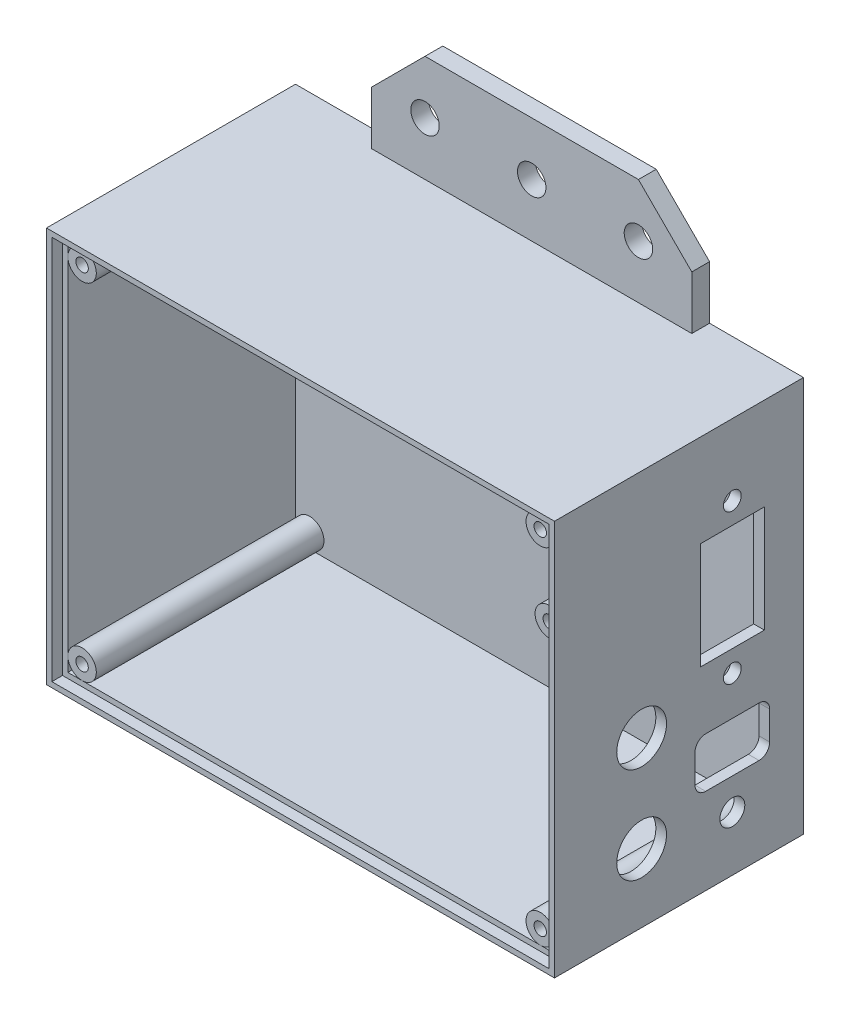
SolidWorks part; units mm, degrees
ref_plane "Alzado" through (0, 0, 0) normal (0, 0, 1) x (1, 0, 0)
ref_plane "Planta" through (0, 0, 0) normal (0, 1, 0) x (1, 0, 0)
ref_plane "Vista lateral" through (0, 0, 0) normal (1, 0, 0) x (0, 0, -1)
sketch "Croquis2" plane through (0, 0, 0) normal (0, 0, 1) x (1, 0, 0)
  line L0 (-57.8, 5) -> (-57.8, -61.2) construction
  line L1 (-57.8, -61.2) -> (5, -61.2) construction
  line L2 (5, -61.2) -> (5, 5) construction
  line L3 (-97.8, -76.2) -> (45, -76.2)
  line L4 (-57.8, 5) -> (5, 5) construction
  line L5 (-97.8, 35) -> (45, 35)
  line L6 (-97.8, 35) -> (-97.8, -76.2)
  line L7 (45, -76.2) -> (45, 35)
  circle A0 centre (0, 0) radius 1.75
  circle A1 centre (-50.8, -11.75) radius 1.75
  circle A2 centre (-16.46, -50.2) radius 1.75
extrude "Saliente-Extruir1" add sketch "Croquis2" along normal blind 3
sketch "Croquis3" plane through (0, 0, 0) normal (0, 0, 1) x (1, 0, 0)
  line L1 (-97.8, 35) -> (45, 35)
  line L2 (-97.8, 35) -> (-97.8, -76.2)
  line L3 (-97.8, -76.2) -> (45, -76.2)
  line L4 (45, 35) -> (45, -76.2)
  line L9 (-94.8, 32) -> (42, 32)
  line L10 (-94.8, 32) -> (-94.8, -73.2)
  line L11 (-94.8, -73.2) -> (42, -73.2)
  line L12 (42, 32) -> (42, -73.2)
  circle A0 centre (-90.8, 28) radius 1.75
  circle A1 centre (-90.8, 28) radius 4
  circle A2 centre (-90.8, -69.2) radius 1.75
  circle A3 centre (-90.8, -69.2) radius 4
  circle A4 centre (38, -69.2) radius 1.75
  circle A5 centre (38, -69.2) radius 4
  circle A6 centre (38, 28) radius 1.75
  circle A7 centre (38, 28) radius 4
extrude "Saliente-Extruir7" add sketch "Croquis3" along normal blind 70 separate body contours A3 A2 | A5 A4 | A7 A6 | A1 A0 | L4 L1 L2 L3 L9 L12 L11 L10
sketch "Croquis4" plane through (0, 0, 0) normal (0, 0, 1) x (1, 0, 0)
  circle A0 centre (-50.8, -11.75) radius 4
  circle A1 centre (-50.8, -11.75) radius 1.75
  circle A2 centre (-16.46, -50.2) radius 1.75
  circle A3 centre (-16.46, -50.2) radius 4
  circle A4 centre (0, 0) radius 1.75
  circle A5 centre (0, 0) radius 4
extrude "Saliente-Extruir8" add sketch "Croquis4" along normal blind 10
sketch "Croquis5" plane through (0, 0, 0) normal (0, 0, 1) x (1, 0, 0)
  circle A0 centre (0, 0) radius 4
  circle A1 centre (-16.46, -50.2) radius 4
  circle A2 centre (-50.8, -11.75) radius 4
extrude "Cortar-Extruir1" cut sketch "Croquis5" along normal blind 1.5
ref_plane "Plano1" through (50, 0, 0) normal (1, 0, 0) x (0, 0, -1)
sketch "Croquis6" plane through (50, 0, 0) normal (1, 0, 0) x (0, 0, -1)
  line L2 (-12.5, -38) -> (-27.5, -38)
  line L3 (-9.5, -41) -> (-9.5, -49)
  line L4 (-12.5, -52) -> (-27.5, -52)
  line L5 (-30.5, -41) -> (-30.5, -49)
  line L6 (-11, 9) -> (-29, 9)
  line L7 (-11, 9) -> (-11, -21)
  line L8 (-11, -21) -> (-29, -21)
  line L9 (-29, 9) -> (-29, -21)
  circle A0 centre (-20, 15) radius 2.5
  circle A1 centre (-20, -27) radius 2.5
  arc A2 (-30.5, -41) -> (-27.5, -38) centre (-27.5, -41) cw
  arc A3 (-9.5, -41) -> (-12.5, -38) centre (-12.5, -41) ccw
  arc A4 (-9.5, -49) -> (-12.5, -52) centre (-12.5, -49) cw
  arc A5 (-27.5, -52) -> (-30.5, -49) centre (-27.5, -49) cw
  circle A6 centre (-45.5, -57) radius 7
  circle A7 centre (-45.5, -30) radius 7
  circle A8 centre (-20, -60.8227) radius 3.5
extrude "Cortar-Extruir2" cut sketch "Croquis6" against normal blind 37.5
ref_plane "Plano2" through (0, 0, 70) normal (0, 0, 1) x (1, 0, 0)
sketch "Croquis7" plane through (0, 0, 70) normal (0, 0, 1) x (1, 0, 0)
  line L9 (-94.8, 33.5) -> (-96.3, 33.5)
  line L10 (-96.3, 32) -> (-96.3, 33.5)
  line L13 (42, -74.7) -> (43.5, -74.7)
  line L14 (43.5, -73.2) -> (43.5, -74.7)
  line L15 (43.5, -74.7) -> (-96.3, -74.7)
  line L16 (43.5, -74.7) -> (43.5, 33.5)
  line L17 (43.5, 33.5) -> (-96.3, 33.5)
  line L18 (-96.3, -74.7) -> (-96.3, 33.5)
extrude "Cortar-Extruir3" cut sketch "Croquis7" against normal blind 3 contours L18 L15 L13 L14 L16 L17 L9 L10
sketch "Croquis8" plane through (0, 0, 0) normal (0, 0, 1) x (1, 0, 0)
  line L0 (-71.4, -76.2) -> (18.6, -76.2)
  line L1 (45, 35) -> (-97.8, 35) construction
  line L2 (-26.4, 65) -> (-56.4, 65)
  line L3 (-71.4, -91.2) -> (-56.4, -106.2)
  line L4 (-56.4, -106.2) -> (3.6, -106.2)
  line L5 (-71.4, 50) -> (-56.4, 65)
  line L6 (-71.4, 50) -> (-71.4, 35)
  line L7 (-71.4, 35) -> (18.6, 35)
  line L8 (18.6, 35) -> (18.6, 50)
  line L9 (-26.4, 65) -> (3.6, 65)
  line L10 (3.6, 65) -> (18.6, 50)
  line L11 (-97.8, 35) -> (45, 35) construction
  line L12 (-71.4, -76.2) -> (-71.4, -91.2)
  line L14 (18.6, -76.2) -> (18.6, -91.2)
  line L15 (18.6, -91.2) -> (3.6, -106.2)
  circle A0 centre (-56.4, 50) radius 4
  circle A1 centre (-26.4, 50) radius 4
  circle A2 centre (3.6, 50) radius 4
  circle A3 centre (-56.4, -91.2) radius 4
  circle A4 centre (-26.4, -91.2) radius 4
  circle A5 centre (3.6, -91.2) radius 4
  dimension "D1" = 171.2
  dimension "D2" = 141.2
  dimension "D3" = 111.2
  dimension "D4" = 142.8
  dimension "D5" = 60
  dimension "D6" = 41.4
  dimension "D7" = 41.4
  dimension "D8" = 30
  dimension "D9" = 15
  dimension "D10" = 71.4
extrude "Saliente-Extruir9" add sketch "Croquis8" along normal blind 5
